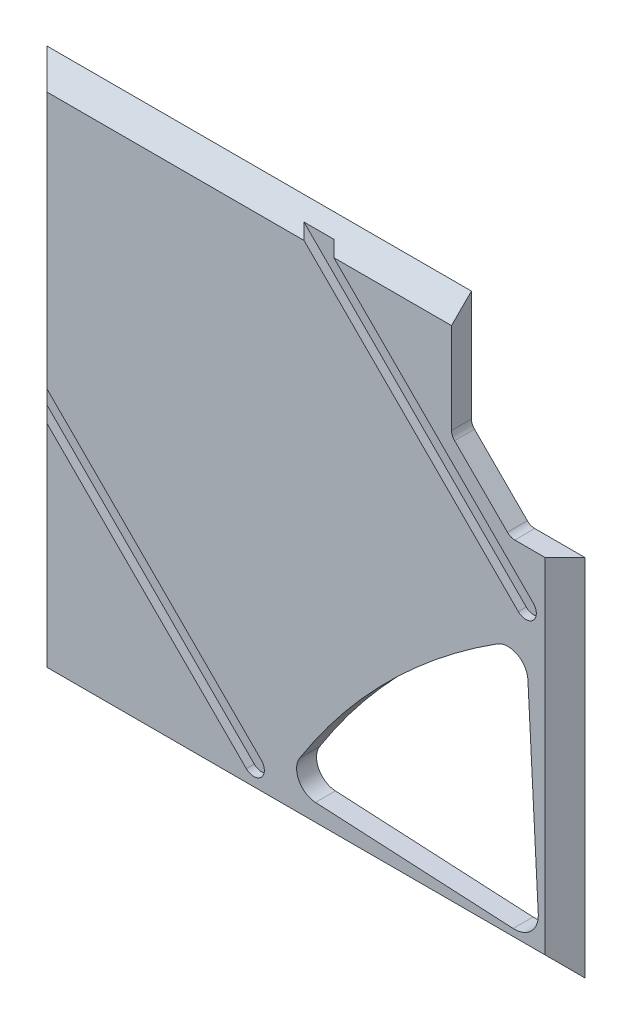
SolidWorks part; units mm, degrees
ref_plane "Front Plane" through (0, 0, 0) normal (0, 0, 1) x (1, 0, 0)
ref_plane "Top Plane" through (0, 0, 0) normal (0, 1, 0) x (1, 0, 0)
ref_plane "Right Plane" through (0, 0, 0) normal (1, 0, 0) x (0, 0, -1)
sketch "Sketch2" plane through (0, 0, 0) normal (0, 0, 1) x (1, 0, 0)
  line L0 (-171.45, 171.45) -> (171.45, -171.45) construction
  line L1 (-171.45, 171.45) -> (171.45, 171.45)
  line L2 (-171.45, 171.45) -> (-171.45, -171.45)
  line L3 (-171.45, -171.45) -> (171.45, -171.45)
  line L4 (171.45, 171.45) -> (171.45, -171.45)
  line L5 (-171.45, -171.45) -> (-171.45, 171.45) construction
  line L6 (-171.45, 171.45) -> (171.45, 171.45) construction
extrude "Boss-Extrude2" add sketch "Sketch2" along normal blind 12.7
draft "Draft2" type of draft neutral plane draft angle 45 faces to draft 4 face at (-171.45, 0, 6.35) face at (0, -171.45, 6.35) face at (171.45, 0, 6.35) face at (0, 171.45, 6.35) neutral plane through (0, 0, 0) neutral plane normal (0, 0, -1) reverse direction yes parameters "D1"=45
sketch "Sketch3" plane through (0, 0, 12.7) normal (0, 0, 1) x (1, 0, 0)
  line L0 (-171.45, 7.6501) -> (-22.1889, -141.6109)
  line L1 (-171.45, 171.45) -> (-171.45, -171.45) construction
  line L4 (-31.708, -151.13) -> (-171.45, -11.388)
  line L5 (-171.45, -11.388) -> (-171.45, 7.6501)
  line L6 (-161.4129, -2.9258) -> (-102.4031, -61.9355) construction
  line L7 (-144.5905, -19.7482) -> (-19.9445, -144.3942) construction
  line L8 (-153.5707, -28.7285) -> (-28.9248, -153.3744) construction
  line L9 (-161.6905, -20.6087) -> (-111.3834, -70.9158) construction
  line L10 (-111.3834, -70.9158) -> (-102.4031, -61.9355) construction
  line L11 (-160.1747, -22.1245) -> (-163.449, -18.8502) construction
  line L12 (-171.45, 171.45) -> (171.45, -171.45) construction
  line L13 (70.9158, 111.3834) -> (61.9355, 102.4031) construction
  line L14 (20.6087, 161.6905) -> (70.9158, 111.3834) construction
  line L15 (2.9258, 161.4129) -> (61.9355, 102.4031) construction
  line L16 (11.388, 171.45) -> (-7.6501, 171.45)
  line L17 (151.13, 31.708) -> (11.388, 171.45)
  line L19 (-7.6501, 171.45) -> (141.6109, 22.1889)
  line L20 (-171.45, -171.45) -> (171.45, -171.45) construction
  line L22 (150.9982, 13.3405) -> (139.4717, 24.867) construction
  line L24 (171.45, -171.45) -> (171.45, 171.45) construction
  arc A0 (-22.1889, -141.6109) -> (-31.708, -151.13) centre (-26.9485, -146.3705) cw
  arc A1 (141.6109, 22.1889) -> (151.13, 31.708) centre (146.3705, 26.9485) ccw
  dimension "D3" = 20.32
  dimension "D4" = 20.32
  dimension "D1" = 0.381
  dimension "D2" = 0.381
extrude "Cut-Extrude1" cut sketch "Sketch3" against normal blind 5.08
sketch "Sketch4" plane through (0, 0, 12.7) normal (0, 0, 1) x (1, 0, 0)
  line L0 (99.06, 171.45) -> (99.06, 100.8819)
  line L1 (171.45, 171.45) -> (-171.45, 171.45) construction
  line L2 (100.9943, 96.2122) -> (134.6932, 62.5133)
  line L3 (139.3629, 60.579) -> (171.45, 60.579)
  line L4 (171.45, -171.45) -> (171.45, 171.45) construction
  line L5 (171.45, 60.579) -> (171.45, 171.45)
  line L6 (171.45, 171.45) -> (99.06, 171.45)
  line L7 (131.1657, 51.689) -> (163.449, 51.689) construction
  line L9 (151.13, 31.708) -> (24.088, 158.75) construction
  line L10 (90.17, 163.449) -> (90.17, 92.6847) construction
  arc A0 (134.6932, 62.5133) -> (139.3629, 60.579) centre (139.3629, 67.183) ccw
  arc A1 (99.06, 100.8819) -> (100.9943, 96.2122) centre (105.664, 100.8819) ccw
  dimension "D4" = 6.604
  dimension "D1" = 8.89
  dimension "D2" = 10.16
  dimension "D3" = 8.89
extrude "Cut-Extrude2" cut sketch "Sketch4" against normal through all
sketch "Sketch5" plane through (0, 0, 0) normal (0, 0, -1) x (-1, 0, 0)
  line L5 (-154.3402, -138.3235) -> (-147.7393, -12.3718)
  line L9 (-12.3718, -147.7393) -> (-138.3235, -154.3402)
  line L10 (-171.45, -171.45) -> (-139.1211, -139.1211) construction
  line L11 (-139.1211, -139.1211) -> (-58.2988, -58.2988) construction
  line L12 (171.45, -171.45) -> (-171.45, -171.45) construction
  line L13 (-58.2988, -58.2988) -> (0, 0) construction
  line L14 (-171.45, -171.45) -> (-171.45, 60.579) construction
  arc A7 (-154.3402, -138.3235) -> (-138.3235, -154.3402) centre (-139.1211, -139.1211) ccw
  arc A8 (-2.3065, -128.2629) -> (-12.3718, -147.7393) centre (-13.0365, -135.0568) cw
  arc A13 (-147.7393, -12.3718) -> (-128.2629, -2.3065) centre (-135.0568, -13.0365) cw
  arc A14 (-128.2629, -2.3065) -> (-2.3065, -128.2629) centre (-345.667, -345.667) cw
  dimension "D1" = 12.7
  dimension "D2" = 15.24
  dimension "D5" = 406.4
  dimension "D3" = 45.72
  dimension "D4" = 3
  dimension "D6" = 114.3
  dimension "D7" = 3
extrude "Cut-Extrude3" cut sketch "Sketch5" against normal through all
